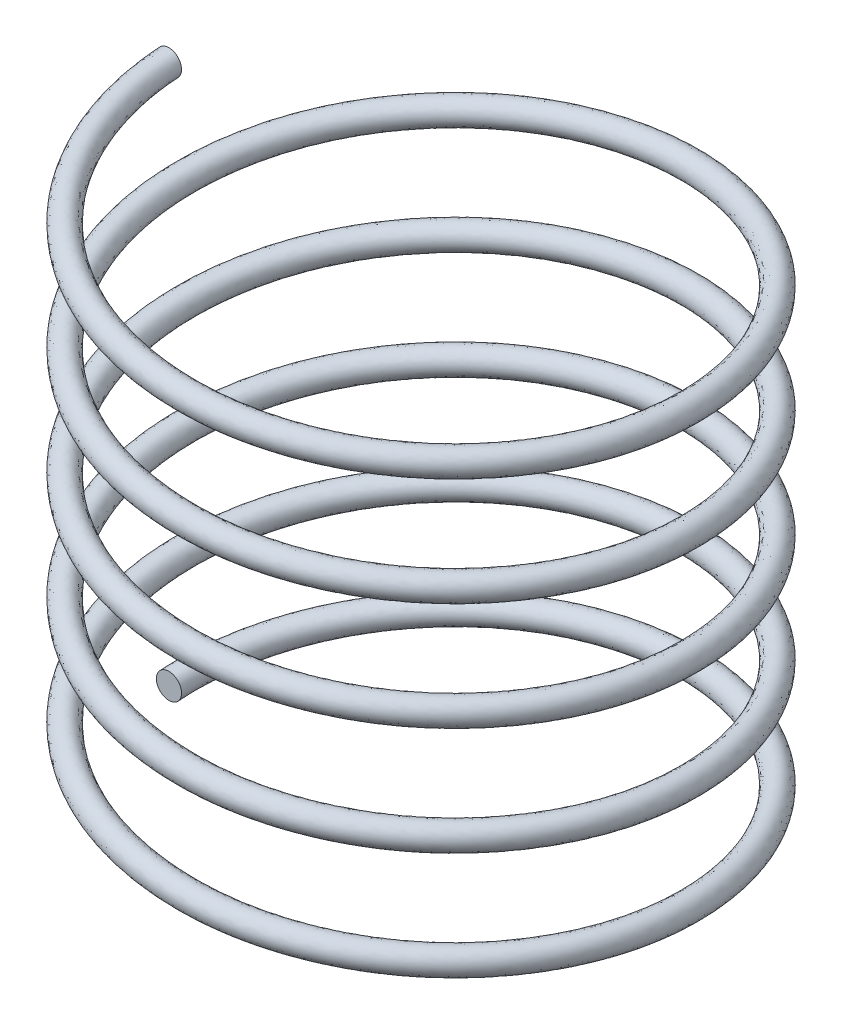
SolidWorks part; units mm, degrees
material "201 Annealed Stainless Steel (SS)"
ref_plane "Front Plane" through (0, 0, 0) normal (0, 0, 1) x (1, 0, 0)
ref_plane "Top Plane" through (0, 0, 0) normal (0, 1, 0) x (1, 0, 0)
ref_plane "Right Plane" through (0, 0, 0) normal (1, 0, 0) x (0, 0, -1)
sketch "Sketch1" plane through (0, 0, 0) normal (0, 0, 1) x (1, 0, 0)
  circle A0 centre (-7, 0) radius 0.35
  dimension "D1" = 0.7
  dimension "D2" = 7
sketch "Sketch4" plane through (0, 0, 0) normal (0, 1, 0) x (1, 0, 0)
  circle A0 centre (0, 0) radius 7.4
  dimension "D1" = 14.8
curve "Helix/Spiral1" pitch 3 height 15 turns 5
sweep "Sweep1" add profiles "Sketch1" path "Helix/Spiral1"
